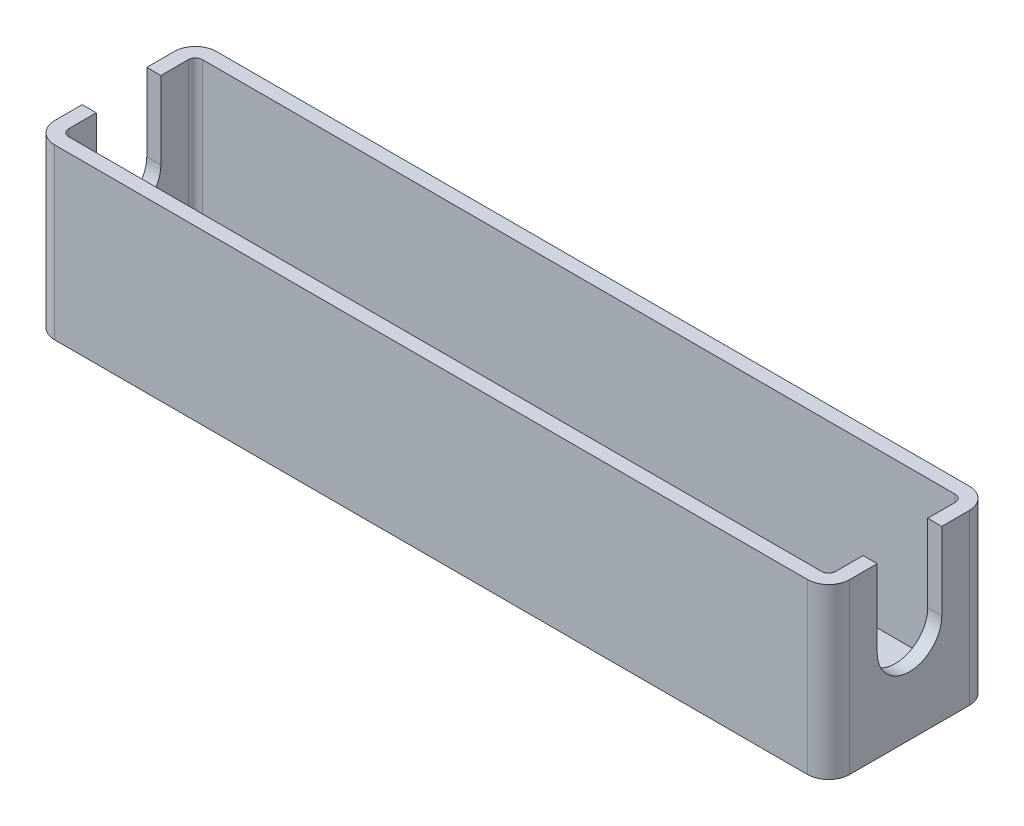
SolidWorks part; units mm, degrees
ref_plane "Front Plane" through (0, 0, 0) normal (0, 0, 1) x (1, 0, 0)
ref_plane "Top Plane" through (0, 0, 0) normal (0, 1, 0) x (1, 0, 0)
ref_plane "Right Plane" through (0, 0, 0) normal (1, 0, 0) x (0, 0, -1)
sketch "Sketch1" plane through (0, 0, 0) normal (0, 1, 0) x (1, 0, 0)
  line L1 (-53.5, -11.5) -> (53.5, -11.5)
  line L2 (-56.5, -8.5) -> (-56.5, 8.5)
  line L3 (-53.5, 11.5) -> (53.5, 11.5)
  line L4 (56.5, -8.5) -> (56.5, 8.5)
  line L5 (-56.5, -11.5) -> (56.5, 11.5) construction
  line L6 (-56.5, 11.5) -> (56.5, -11.5) construction
  arc A0 (-56.5, 8.5) -> (-53.5, 11.5) centre (-53.5, 8.5) cw
  arc A1 (-53.5, -11.5) -> (-56.5, -8.5) centre (-53.5, -8.5) cw
  arc A2 (53.5, -11.5) -> (56.5, -8.5) centre (53.5, -8.5) ccw
  arc A3 (53.5, 11.5) -> (56.5, 8.5) centre (53.5, 8.5) cw
  point P0 (0, 0)
  dimension "D1" = 3
extrude "Boss-Extrude1" add sketch "Sketch1" along normal blind 24
shell "Shell2" thickness 2
sketch "Sketch4" plane through (56.5, 0, 0) normal (1, 0, 0) x (0, 0, -1)
  line L0 (-4.5888, 24) -> (-4.5888, 13)
  line L1 (-8.5, 24) -> (8.5, 24) construction
  line L2 (4.5888, 13) -> (4.5888, 24)
  line L3 (4.5888, 24) -> (-4.5888, 24)
  line L4 (0, 24) -> (0, 20.1621) construction
  line L5 (0, 24) -> (0, 20.7853) construction
  arc A0 (-4.5888, 13) -> (4.5888, 13) centre (0, 13) ccw
  dimension "D1" = 11
extrude "Cut-Extrude1" cut sketch "Sketch4" against normal through all
